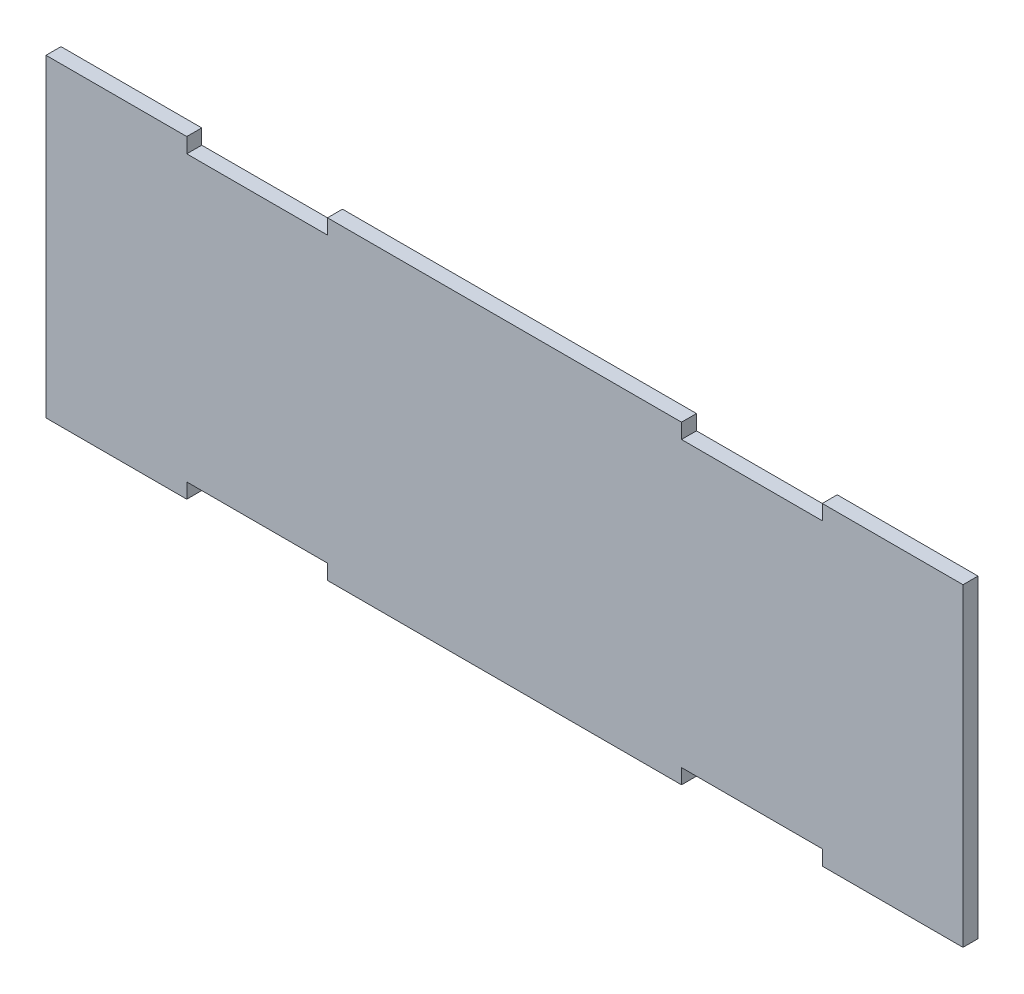
SolidWorks part; units mm, degrees
ref_plane "Front Plane" through (0, 0, 0) normal (0, 0, 1) x (1, 0, 0)
ref_plane "Top Plane" through (0, 0, 0) normal (0, 1, 0) x (1, 0, 0)
ref_plane "Right Plane" through (0, 0, 0) normal (1, 0, 0) x (0, 0, -1)
sketch "Sketch1" plane through (0, 0, 0) normal (0, 0, 1) x (1, 0, 0)
  line L0 (-114.5286, 56.5278) -> (-114.5286, 51.4224) construction
  line L1 (-165.481, -56.6802) -> (165.481, -56.6802)
  line L2 (-165.481, -56.6802) -> (-165.481, 56.6802)
  line L3 (-165.481, 56.6802) -> (165.481, 56.6802)
  line L4 (165.481, -56.6802) -> (165.481, 56.6802)
  line L5 (-165.481, -56.6802) -> (165.481, 56.6802) construction
  line L6 (-165.481, 56.6802) -> (165.481, -56.6802) construction
  line L7 (-114.681, 56.6802) -> (-63.881, 56.6802)
  line L8 (-114.681, 56.6802) -> (-114.681, 51.27)
  line L9 (-114.681, 51.27) -> (-63.881, 51.27)
  line L10 (-63.881, 56.6802) -> (-63.881, 51.27)
  line L11 (63.881, 56.6802) -> (114.681, 56.6802)
  line L12 (63.881, 56.6802) -> (63.881, 51.27)
  line L13 (63.881, 51.27) -> (114.681, 51.27)
  line L14 (114.681, 56.6802) -> (114.681, 51.27)
  line L15 (-114.5286, 51.4224) -> (-64.0334, 51.4224) construction
  line L16 (-64.0334, 56.5278) -> (-64.0334, 51.4224) construction
  line L17 (-114.5286, 56.5278) -> (-64.0334, 56.5278)
  line L18 (64.0334, 56.5278) -> (64.0334, 51.4224) construction
  line L19 (64.0334, 51.4224) -> (114.5286, 51.4224) construction
  line L20 (114.5286, 56.5278) -> (114.5286, 51.4224) construction
  line L21 (64.0334, 56.5278) -> (114.5286, 56.5278)
  line L22 (165.481, 0) -> (-165.481, 0)
  line L23 (114.5286, -56.5278) -> (114.5286, -51.4224) construction
  line L24 (64.0334, -51.4224) -> (114.5286, -51.4224) construction
  line L25 (64.0334, -56.5278) -> (64.0334, -51.4224) construction
  line L26 (-64.0334, -56.5278) -> (-64.0334, -51.4224) construction
  line L27 (-114.5286, -51.4224) -> (-64.0334, -51.4224) construction
  line L28 (-114.5286, -56.5278) -> (-114.5286, -51.4224) construction
  line L29 (64.0334, -56.5278) -> (114.5286, -56.5278)
  line L30 (-114.5286, -56.5278) -> (-64.0334, -56.5278)
  line L31 (114.681, -56.6802) -> (114.681, -51.27)
  line L32 (63.881, -51.27) -> (114.681, -51.27)
  line L33 (63.881, -56.6802) -> (63.881, -51.27)
  line L34 (63.881, -56.6802) -> (114.681, -56.6802)
  line L35 (-63.881, -56.6802) -> (-63.881, -51.27)
  line L36 (-114.681, -51.27) -> (-63.881, -51.27)
  line L37 (-114.681, -56.6802) -> (-114.681, -51.27)
  line L38 (-114.681, -56.6802) -> (-63.881, -56.6802)
  point P0 (0, 0)
  dimension "D2" = 330.962
  dimension "D3" = 50.8
  dimension "D4" = 50.8
  dimension "D5" = 5.4102
  dimension "D6" = 5.4102
  dimension "D7" = 50.8
  dimension "D8" = 50.8
  dimension "D9" = 5.4102
  dimension "D12" = 102.5401
  dimension "D10" = 0.1524
  dimension "D11" = 0.1524
extrude "Boss-Extrude1" add sketch "Sketch1" along normal blind 5.4102 contours L22 L4 L3 L14 L13 L12 L10 L9 L8 L2 | L1 L37 L36 L35 L33 L32 L31 L4 L22 L2
